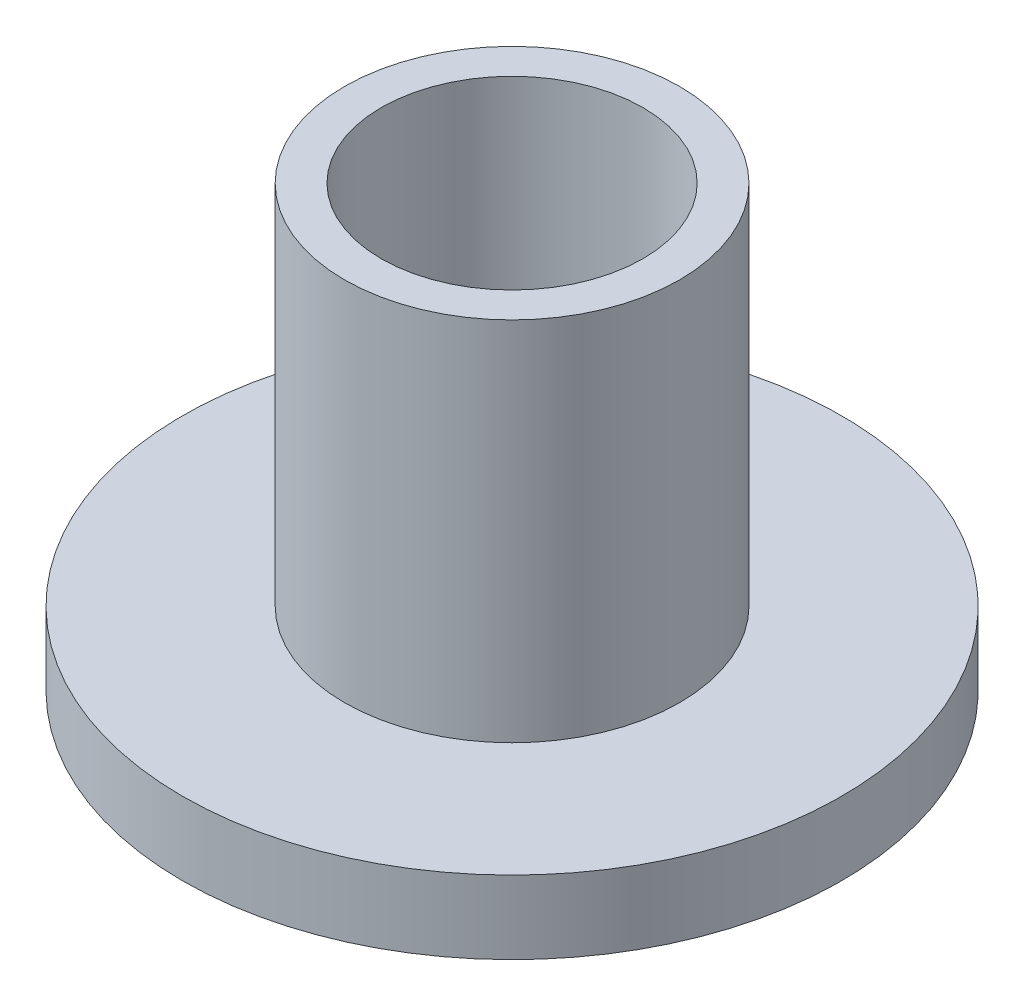
SolidWorks part; units mm, degrees
ref_plane "Front Plane" through (0, 0, 0) normal (0, 0, 1) x (1, 0, 0)
ref_plane "Top Plane" through (0, 0, 0) normal (0, 1, 0) x (1, 0, 0)
ref_plane "Right Plane" through (0, 0, 0) normal (1, 0, 0) x (0, 0, -1)
sketch "Sketch1" plane through (0, 0, 0) normal (0, 1, 0) x (1, 0, 0)
  circle A0 centre (0, 0) radius 9
  circle A1 centre (0, 0) radius 3.575
  dimension "D1" = 18
  dimension "D2" = 7.15
extrude "Boss-Extrude1" add sketch "Sketch1" along normal blind 2
sketch "Sketch2" plane through (0, 2, 0) normal (0, 1, 0) x (1, 0, 0)
  circle A2 centre (0, 0) radius 4.575
  circle A3 centre (0, 0) radius 4.575
  circle M3 centre (0, 0) radius 3.575
  dimension "D1" = 1
extrude "Boss-Extrude2" add sketch "Sketch2" along normal blind 10 contours A3 M3
